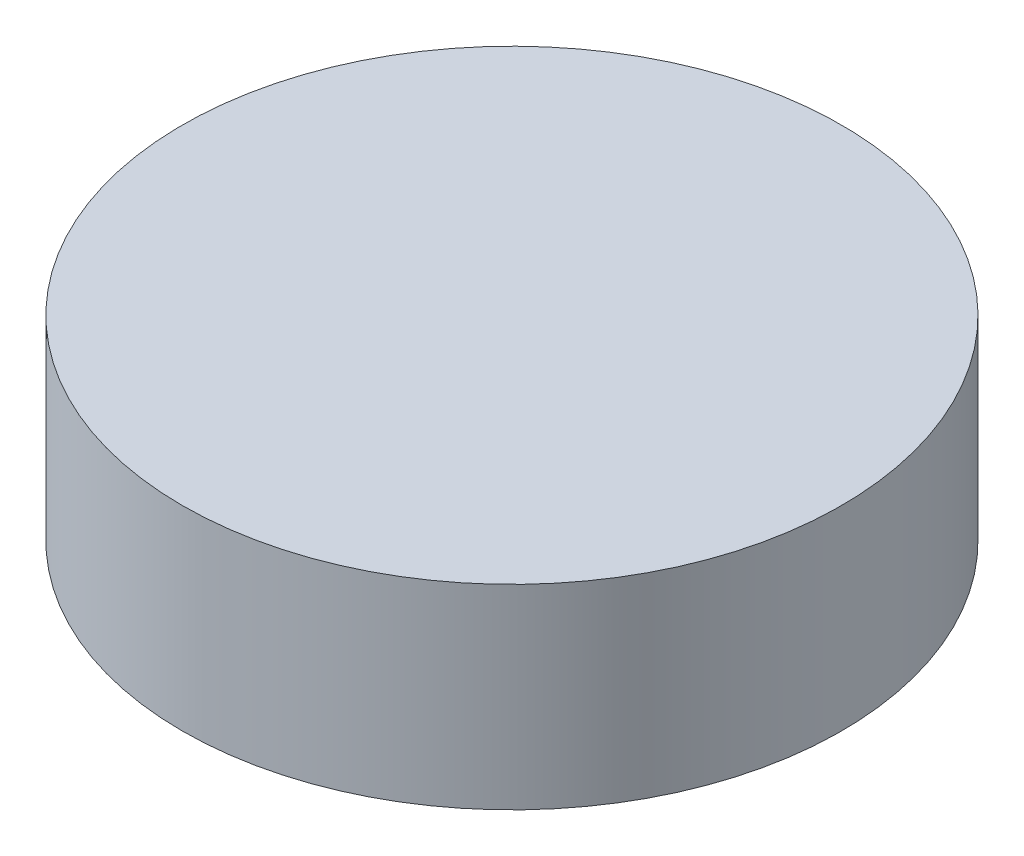
SolidWorks part; units mm, degrees
material "PLA"
ref_plane "Front Plane" through (0, 0, 0) normal (0, 0, 1) x (1, 0, 0)
ref_plane "Top Plane" through (0, 0, 0) normal (0, 1, 0) x (1, 0, 0)
ref_plane "Right Plane" through (0, 0, 0) normal (1, 0, 0) x (0, 0, -1)
sketch "Sketch1" plane through (0, 0, 0) normal (0, 1, 0) x (1, 0, 0)
  circle A0 centre (0, 0) radius 67.5
  dimension "D1" = 135
extrude "Boss-Extrude1" add sketch "Sketch1" along normal blind 40
